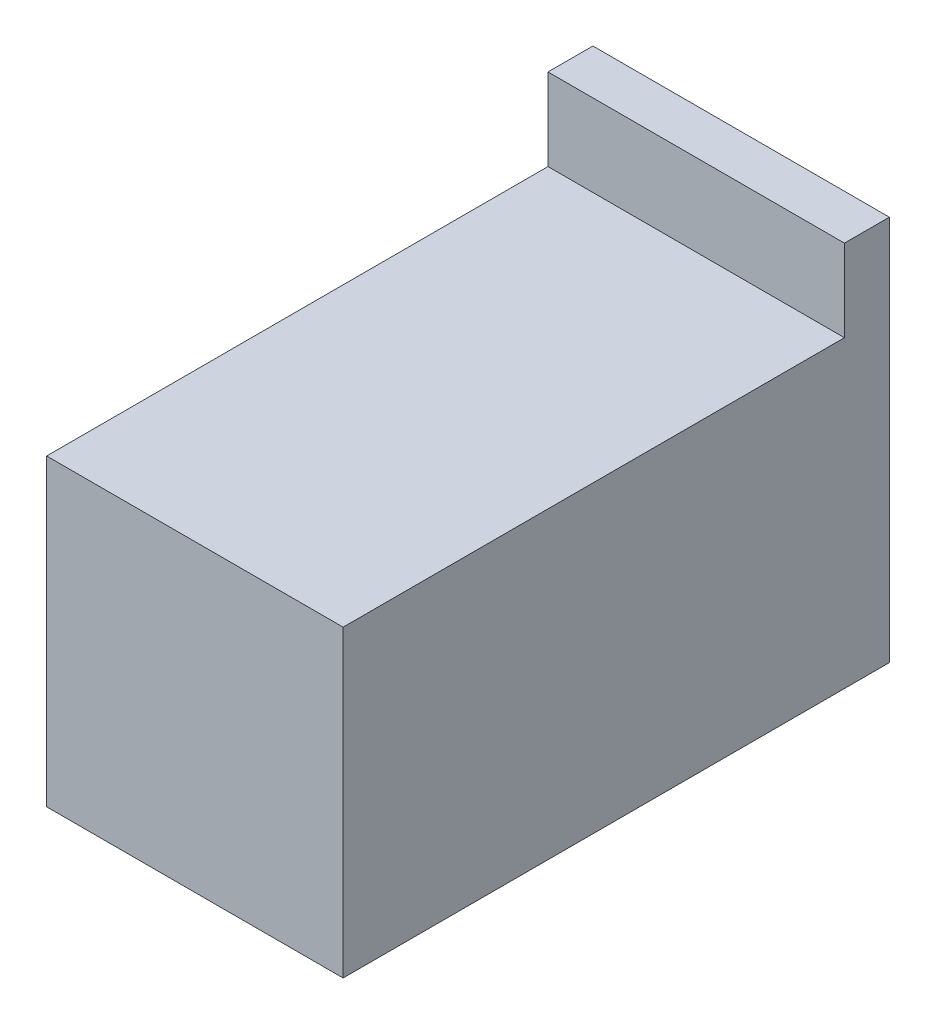
SolidWorks part; units mm, degrees
ref_plane "前视基准面" through (0, 0, 0) normal (0, 0, 1) x (1, 0, 0)
ref_plane "上视基准面" through (0, 0, 0) normal (0, 1, 0) x (1, 0, 0)
ref_plane "右视基准面" through (0, 0, 0) normal (1, 0, 0) x (0, 0, -1)
other "Configuration Table"
sketch "草图1" plane through (0, 0, 0) normal (0, 0, 1) x (1, 0, 0)
  line L1 (-21.71, -22.25) -> (21.71, -22.25)
  line L2 (-21.71, -22.25) -> (-21.71, 22.25)
  line L3 (-21.71, 22.25) -> (21.71, 22.25)
  line L4 (21.71, -22.25) -> (21.71, 22.25)
  line L5 (-21.71, -22.25) -> (21.71, 22.25) construction
  line L6 (-21.71, 22.25) -> (21.71, -22.25) construction
  point P1 (0, 0)
  dimension "D1" = 43.42
  dimension "D2" = 44.5
extrude "凸台-拉伸1" add sketch "草图1" along normal blind 80
sketch "草图3" plane through (0, 22.25, 0) normal (0, 1, 0) x (1, 0, 0)
  line L1 (-21.71, 0) -> (21.71, 0)
  line L2 (-21.71, 0) -> (-21.71, -6.58)
  line L3 (-21.71, -6.58) -> (21.71, -6.58)
  line L4 (21.71, 0) -> (-21.71, 0)
  line L5 (-21.71, 0) -> (-21.71, -80)
  line L6 (-21.71, -80) -> (21.71, -80)
  line L7 (21.71, -80) -> (21.71, 0)
  line L8 (21.71, 0) -> (-21.71, 0)
  line L9 (-21.71, 0) -> (-21.71, -80)
  line L10 (-21.71, -80) -> (21.71, -80)
  line L11 (21.71, -80) -> (21.71, 0)
  line L12 (21.71, 0) -> (21.71, -6.58)
  line M5 (21.71, 0) -> (-21.71, 0)
  line M6 (-21.71, 0) -> (-21.71, -80)
  line M8 (21.71, -80) -> (21.71, 0)
  dimension "D2" = 6.58
  dimension "D1" = 0
extrude "凸台-拉伸2" add sketch "草图3" along normal blind 12 contours L3 M6 M8 M5
